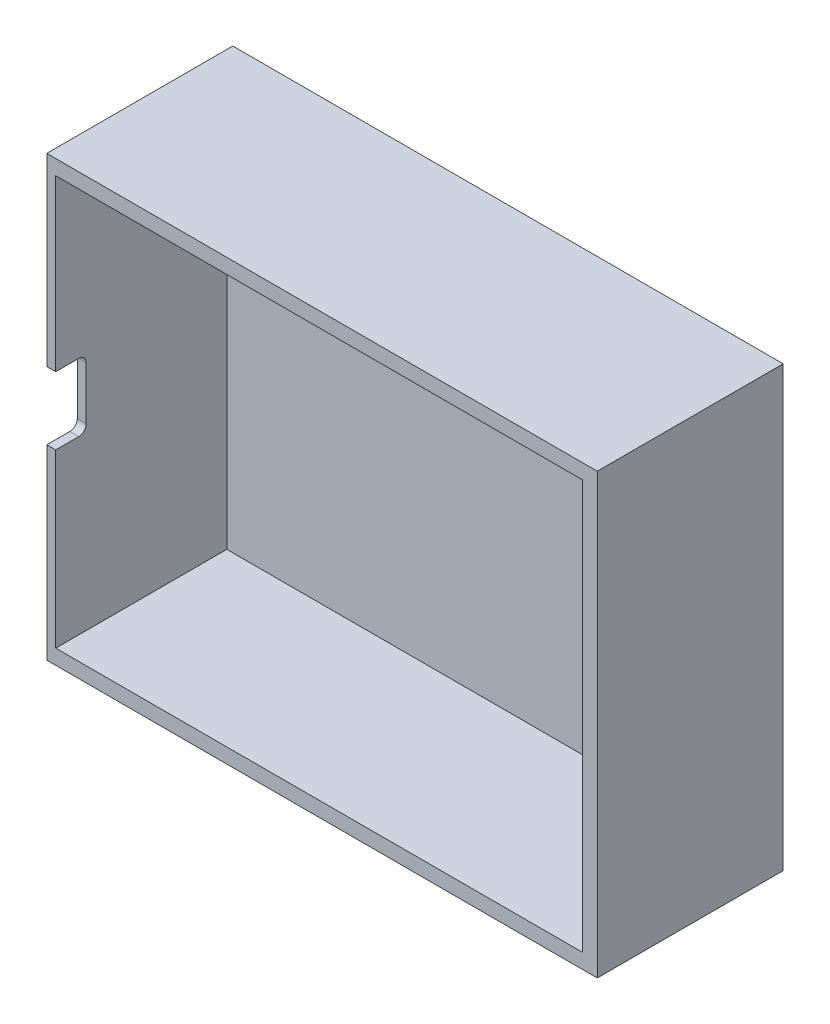
SolidWorks part; units mm, degrees
ref_plane "Alzado" through (0, 0, 0) normal (0, 0, 1) x (1, 0, 0)
ref_plane "Planta" through (0, 0, 0) normal (0, 1, 0) x (1, 0, 0)
ref_plane "Vista lateral" through (0, 0, 0) normal (1, 0, 0) x (0, 0, -1)
sketch "Croquis1" plane through (0, 0, 0) normal (0, 0, 1) x (1, 0, 0)
  line L1 (590.712, 17.7518) -> (664.712, 17.7518)
  line L2 (590.712, 17.7518) -> (590.712, -41.2482)
  line L3 (590.712, -41.2482) -> (664.712, -41.2482)
  line L4 (664.712, 17.7518) -> (664.712, -41.2482)
  dimension "D1" = 74
  dimension "D2" = 59
extrude "Saliente-Extruir1" add sketch "Croquis1" along normal blind 25
shell "Vaciado1" thickness 2
sketch "Croquis2" plane through (590.712, 0, 0) normal (-1, 0, 0) x (0, 0, 1)
  line L1 (21.9, -7.0723) -> (25, -7.0723)
  line L2 (20.9, -8.0723) -> (20.9, -15.1723)
  line L3 (21.9, -16.1723) -> (25, -16.1723)
  line L4 (25, -7.0723) -> (25, -16.1723)
  line L7 (20.9, -8.4023) -> (20.9, -14.8423) construction
  line L8 (25, 17.7518) -> (25, -41.2482) construction
  arc A0 (20.9, -8.0723) -> (21.9, -7.0723) centre (21.9, -8.0723) cw
  arc A1 (20.9, -15.1723) -> (21.9, -16.1723) centre (21.9, -15.1723) ccw
  point P4 (20.9, -11.6223)
  dimension "D3" = 1
  dimension "D1" = 9.1
  dimension "D2" = 4.55
extrude "Cortar-Extruir1" cut sketch "Croquis2" against normal blind 1.2
